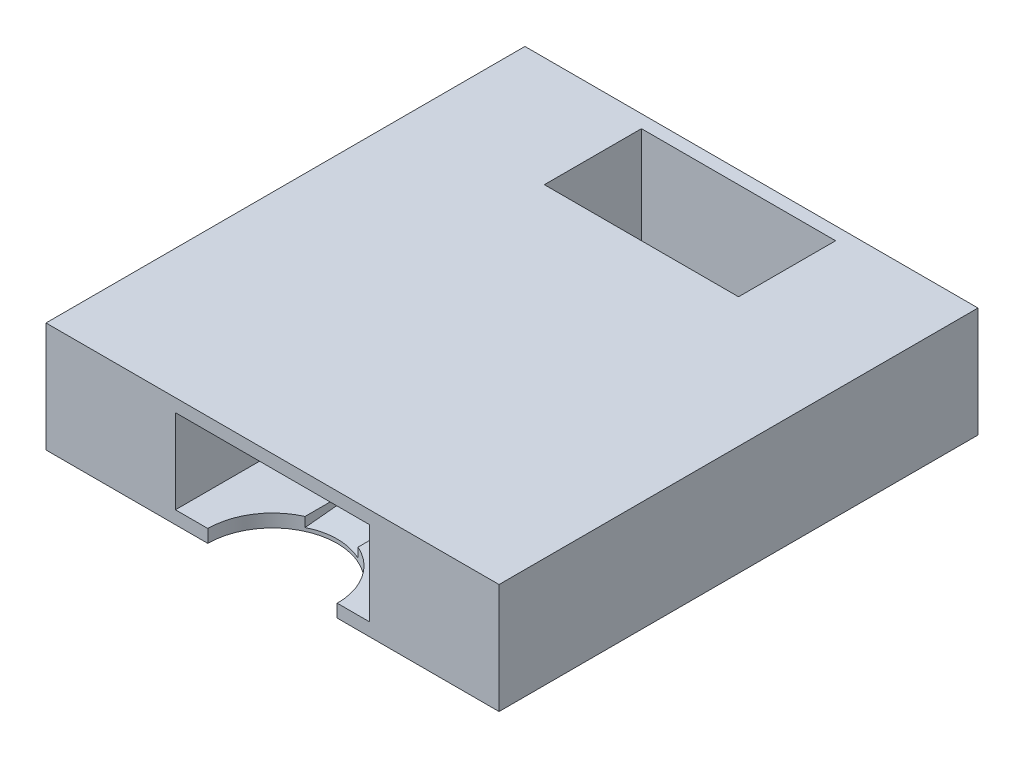
SolidWorks part; units mm, degrees
ref_plane "Alzado" through (0, 0, 0) normal (0, 0, 1) x (1, 0, 0)
ref_plane "Planta" through (0, 0, 0) normal (0, 1, 0) x (1, 0, 0)
ref_plane "Vista lateral" through (0, 0, 0) normal (1, 0, 0) x (0, 0, -1)
sketch "Croquis1" plane through (0, 0, 0) normal (0, 1, 0) x (1, 0, 0)
  line L1 (-35, -50) -> (35, -50)
  line L2 (-35, -50) -> (-35, 50)
  line L3 (-35, 50) -> (35, 50)
  line L4 (35, -50) -> (35, 50)
  line L5 (-35, -50) -> (35, 50) construction
  line L6 (-35, 50) -> (35, -50) construction
  point P0 (0, 0)
  dimension "D1" = 70
  dimension "D2" = 100
extrude "Saliente-Extruir1" add sketch "Croquis1" along normal blind 15
sketch "Croquis2" plane through (0, 0, 50) normal (0, 0, 1) x (1, 0, 0)
  line L0 (0, 15) -> (0, 6.9528) construction
  line L1 (-35, 15) -> (35, 15) construction
  line L2 (-15, 2) -> (15, 2)
  line L3 (-15, 2) -> (-15, 15)
  line L4 (-15, 15) -> (15, 15)
  line L5 (15, 15) -> (15, 2)
  point P8 (0, 2)
  dimension "D1" = 13
  dimension "D2" = 30
extrude "Cortar-Extruir1" cut sketch "Croquis2" against normal blind 72
sketch "Croquis3" plane through (0, 0, 0) normal (0, -1, 0) x (1, 0, 0)
  line L0 (-35, 50) -> (35, 50) construction
  line L1 (-10, 50) -> (10, 50)
  arc A0 (10, 50) -> (-10, 50) centre (0, 50) cw
  dimension "D1" = 10
extrude "Cortar-Extruir2" cut sketch "Croquis3" against normal blind 72
sketch "Croquis4" plane through (0, 2, 0) normal (0, 1, 0) x (1, 0, 0)
  line L0 (0, -40) -> (0, -36.2475) construction
  line L6 (-4.5, -34.2619) -> (4.5, -34.2619)
  line L7 (-4.5, -34.2619) -> (-4.5, -35.8619)
  line L9 (0, -35.8471) -> (0, -34.2767) construction
  line L10 (-4.5, -35.8619) -> (4.5, -35.8619)
  line L11 (4.5, -34.2619) -> (4.5, -35.8619)
  line L12 (-4.5, -34.2619) -> (4.5, -35.8619) construction
  line L13 (-4.5, -35.8619) -> (4.5, -34.2619) construction
  arc A0 (10, -50) -> (-10, -50) centre (0, -50) ccw construction
  point P0 (0, -35.0619)
  dimension "D1" = 1.6
  dimension "D2" = 4.5
  dimension "D3" = 4.5
extrude "Cortar-Extruir3" cut sketch "Croquis4" against normal blind 2
sketch "Croquis6" plane through (0, 0, 35.8619) normal (0, 0, -1) x (-1, 0, 0)
  line L0 (-4.5, 2) -> (4.5, 2) construction
  line L1 (-4.1, 3) -> (4.1, 3)
  line L2 (-4.1, 3) -> (-4.1, 1)
  line L3 (-4.1, 1) -> (4.1, 1)
  line L4 (4.1, 3) -> (4.1, 1)
  line L5 (-4.1, 3) -> (4.1, 1) construction
  line L6 (-4.1, 1) -> (4.1, 3) construction
  line L7 (0, 2) -> (0, 4.2492) construction
  point P0 (0, 2)
  dimension "D1" = 2
  dimension "D2" = 8.2
extrude "Cortar-Extruir4" cut sketch "Croquis6" against normal through all
sketch "Croquis7" plane through (-4.1, 0, 0) normal (1, 0, 0) x (0, 0, -1)
  line L4 (-40.8791, 1) -> (-35.8619, 1) construction
  line L5 (-40.8791, 0.5104) -> (-35.8619, 1)
  line L6 (-35.8619, 1) -> (-40.8791, 1)
  line L7 (-40.8791, 1) -> (-40.8791, 0.5104)
extrude "Cortar-Extruir5" cut sketch "Croquis7" along normal blind 8.2
sketch "Croquis8" plane through (0, 15, 0) normal (0, 1, 0) x (1, 0, 0)
  line L0 (-35, -50) -> (35, -50)
  line L1 (35, -50) -> (35, 7)
  line L2 (35, 7) -> (-35, 7)
  line L3 (-35, 7) -> (-35, -50)
  line L4 (-15, 22) -> (15, 22) construction
  line L5 (15, 22) -> (35, 22)
  line L6 (35, -50) -> (35, 50) construction
  line L7 (35, 22) -> (35, 27.5497)
  line L8 (35, 27.5497) -> (-35, 27.5497)
  line L9 (-35, 50) -> (-35, -50) construction
  line L10 (-35, 27.5497) -> (-35, 22)
  line L11 (-35, 22) -> (15, 22)
  dimension "D1" = 15
extrude "Saliente-Extruir3" add sketch "Croquis8" along normal blind 2
sketch "Croquis9" plane through (0, 15, 0) normal (0, 1, 0) x (1, 0, 0)
  line L0 (-15, 22) -> (-15, 7)
  line L1 (-15, 7) -> (-35, 7)
  line L2 (-35, 7) -> (-35, 22)
  line L3 (-35, 22) -> (-15, 22)
  line L4 (15, 7) -> (35, 7)
  line L5 (35, 7) -> (35, 22)
  line L6 (35, 22) -> (15, 22)
  line L7 (15, 22) -> (15, 7)
extrude "Saliente-Extruir4" add sketch "Croquis9" along normal blind 2
sketch "Croquis10" plane through (0, 15, 0) normal (0, 1, 0) x (1, 0, 0)
  line L0 (-35, 27.5497) -> (35, 27.5497)
  line L1 (35, 27.5497) -> (35, 50)
  line L2 (35, 50) -> (-35, 50)
  line L3 (-35, 50) -> (-35, 27.5497)
extrude "Saliente-Extruir5" add sketch "Croquis10" along normal blind 2
sketch "Croquis12" plane through (0, 17, 0) normal (0, 1, 0) x (1, 0, 0)
  line L0 (35, -50) -> (35, 50) construction
  line L1 (-35, 50) -> (35, 50)
  line L2 (-35, 50) -> (-35, 24)
  line L3 (-35, 24) -> (35, 24)
  line L4 (35, 50) -> (35, 24)
  line L5 (-15, 22) -> (15, 22) construction
  dimension "D1" = 2
extrude "Cortar-Extruir6" cut sketch "Croquis12" against normal through all
